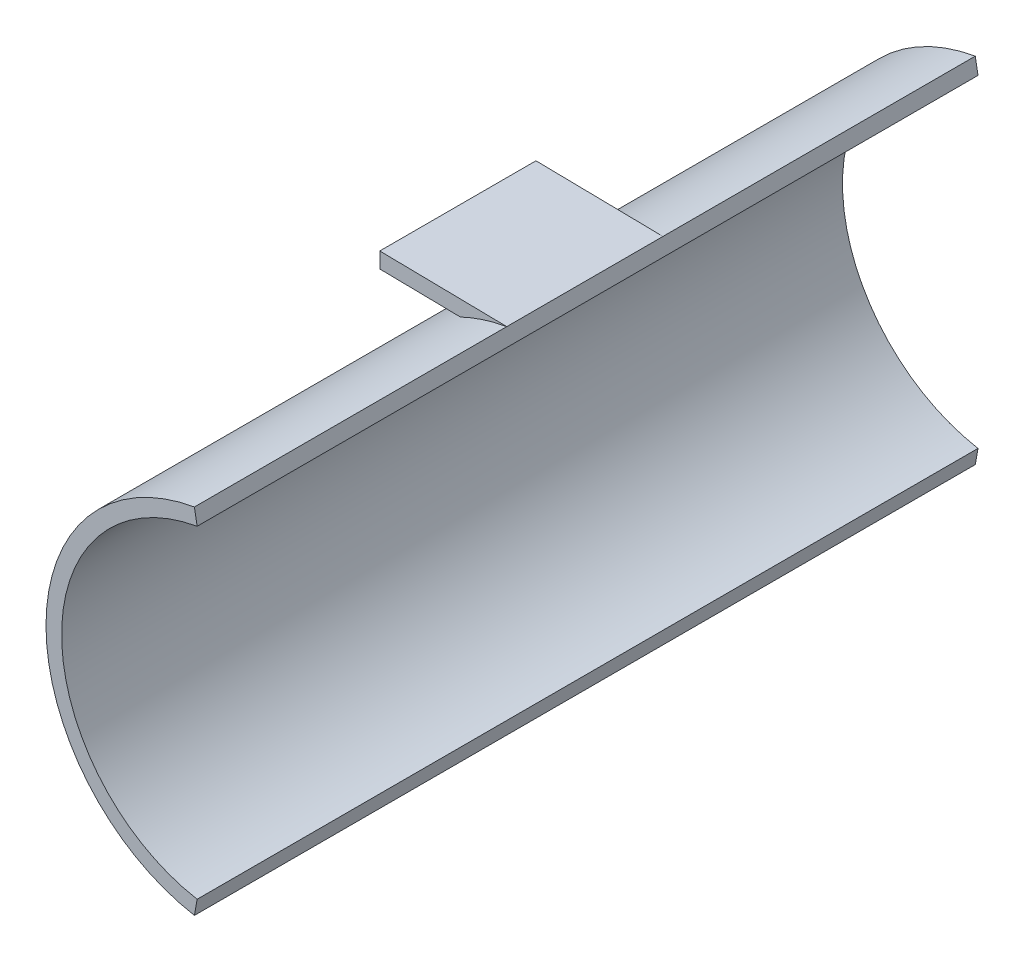
SolidWorks part; units mm, degrees
ref_plane "前视基准面" through (0, 0, 0) normal (0, 0, 1) x (1, 0, 0)
ref_plane "上视基准面" through (0, 0, 0) normal (0, 1, 0) x (1, 0, 0)
ref_plane "右视基准面" through (0, 0, 0) normal (1, 0, 0) x (0, 0, -1)
sketch "草图1" plane through (0, 0, 0) normal (0, 0, 1) x (1, 0, 0)
  line L2 (0, 0) -> (5.3806, 0) construction
  line L3 (-3.6466, 20.681) -> (-3.9939, 22.6506)
  line L4 (-3.6466, -20.681) -> (-3.9939, -22.6506)
  arc A0 (-3.9939, 22.6506) -> (-3.9939, -22.6506) centre (0, 0) ccw
  arc A1 (-3.6466, 20.681) -> (-3.6466, -20.681) centre (0, 0) ccw
  dimension "D1" = 42
  dimension "D2" = 46
extrude "凸台-拉伸1" add sketch "草图1" along normal mid plane 100
sketch "草图2" plane through (0, 0, 0) normal (0, 0, 1) x (1, 0, 0)
  line L0 (-3.9939, 22.6506) -> (-20.2547, 22.9116)
  line L1 (-20.2547, 22.9116) -> (-20.2547, 20.9116)
  line L2 (-20.2547, 20.9116) -> (-9.9302, 20.7459)
  arc A0 (-3.9939, 22.6506) -> (-3.9939, -22.6506) centre (0, 0) ccw construction
  arc A1 (-3.9939, 22.6506) -> (-9.9302, 20.7459) centre (0, 0) ccw
  dimension "D1" = 2
extrude "凸台-拉伸2" add sketch "草图2" along normal mid plane 20
